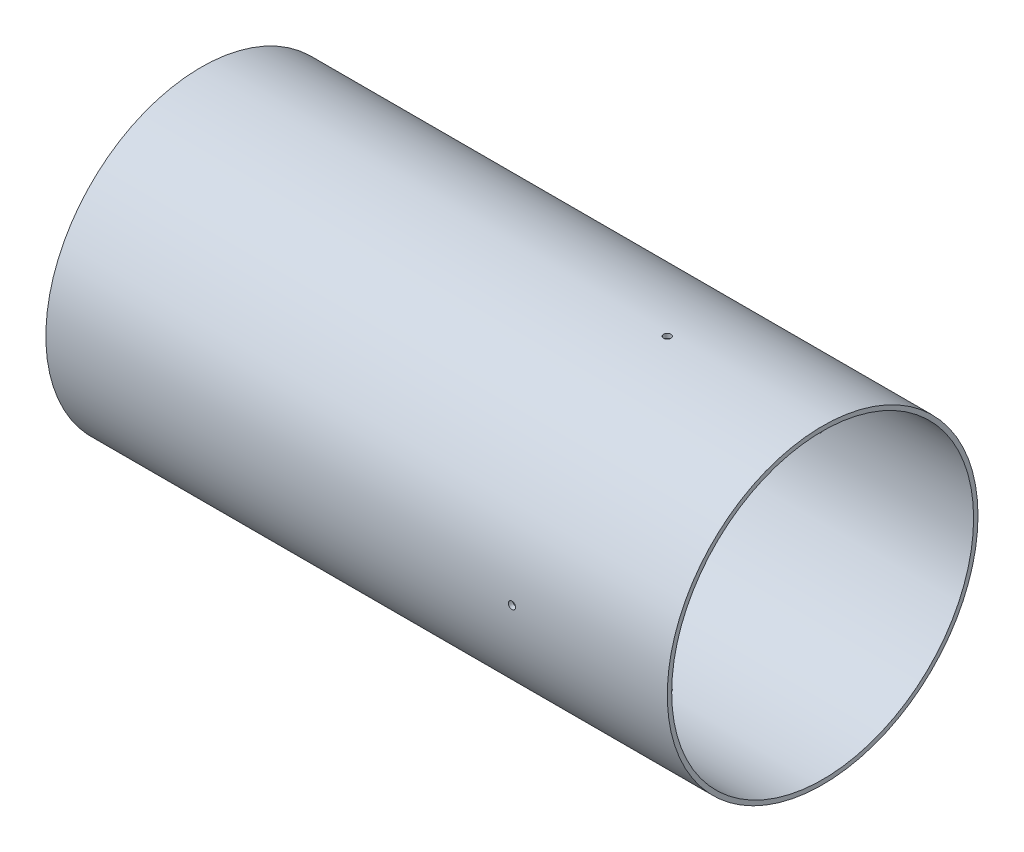
SolidWorks part; units mm, degrees
material "E-Glass Fiber"
ref_plane "Front Plane" through (0, 0, 0) normal (0, 0, 1) x (1, 0, 0)
ref_plane "Top Plane" through (0, 0, 0) normal (0, 1, 0) x (1, 0, 0)
ref_plane "Right Plane" through (0, 0, 0) normal (1, 0, 0) x (0, 0, -1)
sketch "Sketch1" plane through (0, 0, 0) normal (1, 0, 0) x (0, 0, -1)
  circle A0 centre (0, 0) radius 74.041
  circle A1 centre (0, 0) radius 76.2
  dimension "D1" = 152.4
  dimension "D2" = 2.159
extrude "Boss-Extrude1" add sketch "Sketch1" along normal blind 304.8
sketch "Sketch2" plane through (0, 0, 0) normal (0, 0, 1) x (1, 0, 0)
  line L0 (304.8, -76.2) -> (304.8, 76.2) construction
  circle A0 centre (228.6, 0) radius 1.7859
  point P4 (0, 0)
  dimension "D1" = 3.5719
  dimension "D2" = 76.2
extrude "Cut-Extrude1" cut sketch "Sketch2" against normal up to surface (76.2 mm away) up to face at (304.8, 0, -76.2)
pattern_circular "CirPattern1" count 4 over 360 about axis through (0, 0, 0) along (1, 0, 0) of "Cut-Extrude1"
